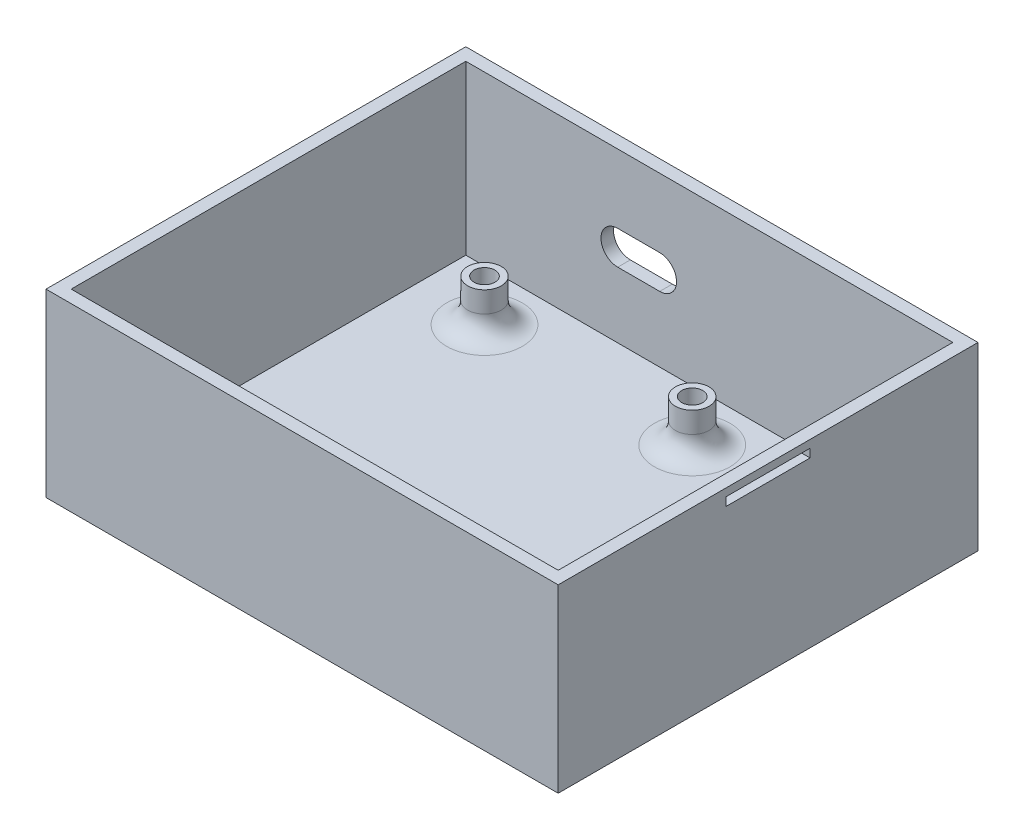
SolidWorks part; units mm, degrees
ref_plane "Front Plane" through (0, 0, 0) normal (0, 0, 1) x (1, 0, 0)
ref_plane "Top Plane" through (0, 0, 0) normal (0, 1, 0) x (1, 0, 0)
ref_plane "Right Plane" through (0, 0, 0) normal (1, 0, 0) x (0, 0, -1)
sketch "Sketch1" plane through (0, 0, 0) normal (0, 1, 0) x (1, 0, 0)
  line L1 (-61, -50) -> (61, -50)
  line L2 (-61, -50) -> (-61, 50)
  line L3 (-61, 50) -> (61, 50)
  line L4 (61, -50) -> (61, 50)
  line L5 (-61, -50) -> (61, 50) construction
  line L6 (-61, 50) -> (61, -50) construction
  point P0 (0, 0)
  dimension "D1" = 122
  dimension "D2" = 100
extrude "Boss-Extrude1" add sketch "Sketch1" along normal blind 3
ref_plane "Plane1" through (0, 38, 0) normal (0, 1, 0) x (1, 0, 0)
sketch "Sketch2" plane through (0, 38, 0) normal (0, 1, 0) x (1, 0, 0)
  line L1 (-61, -50) -> (61, -50)
  line L2 (-61, -50) -> (-61, 50)
  line L3 (-61, 50) -> (61, 50)
  line L4 (61, -50) -> (61, 50)
  line L5 (-61, -50) -> (61, 50) construction
  line L6 (-61, 50) -> (61, -50) construction
  point P0 (0, 0)
extrude "Boss-Extrude2" add sketch "Sketch2" along normal blind 5 separate body
loft "Loft1" add section face at (0, 3, 0) section face at (0, 38, 0)
shell "Shell1" thickness 3
sketch "Sketch5" plane through (-61, 0, 0) normal (-1, 0, 0) x (0, 0, 1)
  line L0 (-50, 43) -> (-50, 40.2185) construction
  line L1 (-50, 43) -> (-50, 0) construction
  line L2 (-50, 40.2185) -> (50, 40.2185) construction
  line L3 (50, 43) -> (50, 0) construction
  line L4 (-0.5043, 43) -> (-0.5043, 41.25) construction
  line L5 (-10, 39.2185) -> (10, 39.2185)
  line L6 (-10, 39.2185) -> (-10, 41.2185)
  line L7 (-10, 41.2185) -> (10, 41.2185)
  line L8 (10, 39.2185) -> (10, 41.2185)
  line L9 (-10, 39.2185) -> (10, 41.2185) construction
  line L10 (-10, 41.2185) -> (10, 39.2185) construction
  line L11 (-50, 43) -> (50, 43) construction
  point P5 (0, 40.2185)
  dimension "D1" = 20
  dimension "D2" = 2
  dimension "D3" = 1.75
extrude "Cut-Extrude1" cut sketch "Sketch5" against normal blind 2.4
sketch "Sketch6" plane through (61, 0, 0) normal (1, 0, 0) x (0, 0, -1)
  line L0 (-50, 43) -> (-50, 40.1771) construction
  line L1 (-50, 43) -> (-50, 0) construction
  line L2 (-50, 40.1771) -> (50, 40.1771) construction
  line L3 (50, 43) -> (50, 0) construction
  line L4 (0, 43) -> (0, 41.25) construction
  line L5 (-10, 39.1771) -> (10, 39.1771)
  line L6 (-10, 39.1771) -> (-10, 41.1771)
  line L7 (-10, 41.1771) -> (10, 41.1771)
  line L8 (10, 39.1771) -> (10, 41.1771)
  line L9 (-10, 39.1771) -> (10, 41.1771) construction
  line L10 (-10, 41.1771) -> (10, 39.1771) construction
  line L12 (-50, 43) -> (50, 43) construction
  point P8 (0, 40.1771)
  dimension "D1" = 20
  dimension "D2" = 2
extrude "Cut-Extrude2" cut sketch "Sketch6" against normal blind 2.4
sketch "Sketch7" plane through (0, 3, 0) normal (0, 1, 0) x (1, 0, 0)
  line L1 (-46.6265, -38.9829) -> (13.3735, -38.9829) construction
  line L2 (-46.6265, -38.9829) -> (-46.6265, 41.869) construction
  line L3 (-46.6265, 41.869) -> (13.3735, 41.869) construction
  line L4 (13.3735, -38.9829) -> (13.3735, 41.869) construction
  line L5 (-46.6265, -38.9829) -> (13.3735, 41.869) construction
  line L6 (-46.6265, 41.869) -> (13.3735, -38.9829) construction
  circle A0 centre (-41.4536, 34.8983) radius 4
  circle A1 centre (8.1302, 34.8034) radius 4
  circle A2 centre (8.1765, -31.9798) radius 4
  circle A3 centre (-41.4001, -31.9401) radius 4
  point P0 (-16.6265, 1.4431)
  dimension "D1" = 60
  dimension "D2" = 80.8519
extrude "Boss-Extrude3" add sketch "Sketch7" along normal blind 10
sketch "Sketch11" plane through (0, 13, 0) normal (0, 1, 0) x (1, 0, 0)
  circle A0 centre (-41.4001, -31.9401) radius 2.5
  circle A1 centre (8.1765, -31.9798) radius 2.5
  circle A2 centre (8.1302, 34.8034) radius 2.5
  circle A3 centre (-41.4536, 34.8983) radius 2.5
  dimension "D1" = 5
  dimension "D2" = 5
  dimension "D3" = 5
  dimension "D4" = 5
extrude "Cut-Extrude5" cut sketch "Sketch11" against normal blind 7
sketch "Sketch12" plane through (0, 0, -47) normal (0, 0, 1) x (1, 0, 0)
  line L1 (-21.8135, 18.6232) -> (-11.8135, 18.6232)
  line L2 (-21.8135, 18.6232) -> (-21.8135, 26.6232) construction
  line L3 (-21.8135, 26.6232) -> (-11.8135, 26.6232)
  line L4 (-11.8135, 18.6232) -> (-11.8135, 26.6232) construction
  line L5 (-21.8135, 18.6232) -> (-11.8135, 26.6232) construction
  line L6 (-21.8135, 26.6232) -> (-11.8135, 18.6232) construction
  arc A0 (-11.8135, 26.6232) -> (-11.8135, 18.6232) centre (-11.8135, 22.6232) cw
  arc A1 (-21.8135, 18.6232) -> (-21.8135, 26.6232) centre (-21.8135, 22.6232) cw
  point P0 (-16.8135, 22.6232)
  dimension "D1" = 10
  dimension "D2" = 8
extrude "Cut-Extrude6" cut sketch "Sketch12" against normal blind 3
sketch "Sketch13" plane through (0, 3, 0) normal (0, 1, 0) x (1, 0, 0)
  line L1 (28.3564, -5.9994) -> (46.3564, -5.9994)
  line L2 (28.3564, -5.9994) -> (28.3564, 38.0006)
  line L3 (28.3564, 38.0006) -> (46.3564, 38.0006)
  line L4 (46.3564, -5.9994) -> (46.3564, 38.0006)
  line L5 (28.3564, -5.9994) -> (46.3564, 38.0006) construction
  line L6 (28.3564, 38.0006) -> (46.3564, -5.9994) construction
  point P0 (37.3564, 16.0006)
  dimension "D1" = 18
  dimension "D2" = 44
extrude "Boss-Extrude5" add sketch "Sketch13" along normal blind 3
sketch "Sketch14" plane through (0, 6, 0) normal (0, 1, 0) x (1, 0, 0)
  line L0 (46.3564, 38.0006) -> (28.3564, 38.0006) construction
  line L1 (29.3564, -4.9994) -> (45.3564, -4.9994)
  line L2 (29.3564, -4.9994) -> (29.3564, 37.0006)
  line L3 (29.3564, 37.0006) -> (45.3564, 37.0006)
  line L4 (45.3564, -4.9994) -> (45.3564, 37.0006)
  line L5 (29.3564, -4.9994) -> (45.3564, 37.0006) construction
  line L6 (29.3564, 37.0006) -> (45.3564, -4.9994) construction
  line L7 (46.3564, -5.9994) -> (46.3564, 38.0006) construction
  line L8 (28.3564, -5.9994) -> (46.3564, -5.9994) construction
  line L9 (28.3564, 38.0006) -> (28.3564, -5.9994) construction
  point P0 (37.3564, 16.0006)
  dimension "D1" = 1
  dimension "D2" = 1
  dimension "D3" = 1
  dimension "D4" = 1
extrude "Cut-Extrude7" cut sketch "Sketch14" against normal blind 3
fillet "Fillet1" radius 5 4 edges at (8.1765, 3, 27.9798) (-41.4001, 3, 27.9401) (8.1302, 3, -38.8034) (-41.4536, 3, -38.8983)
